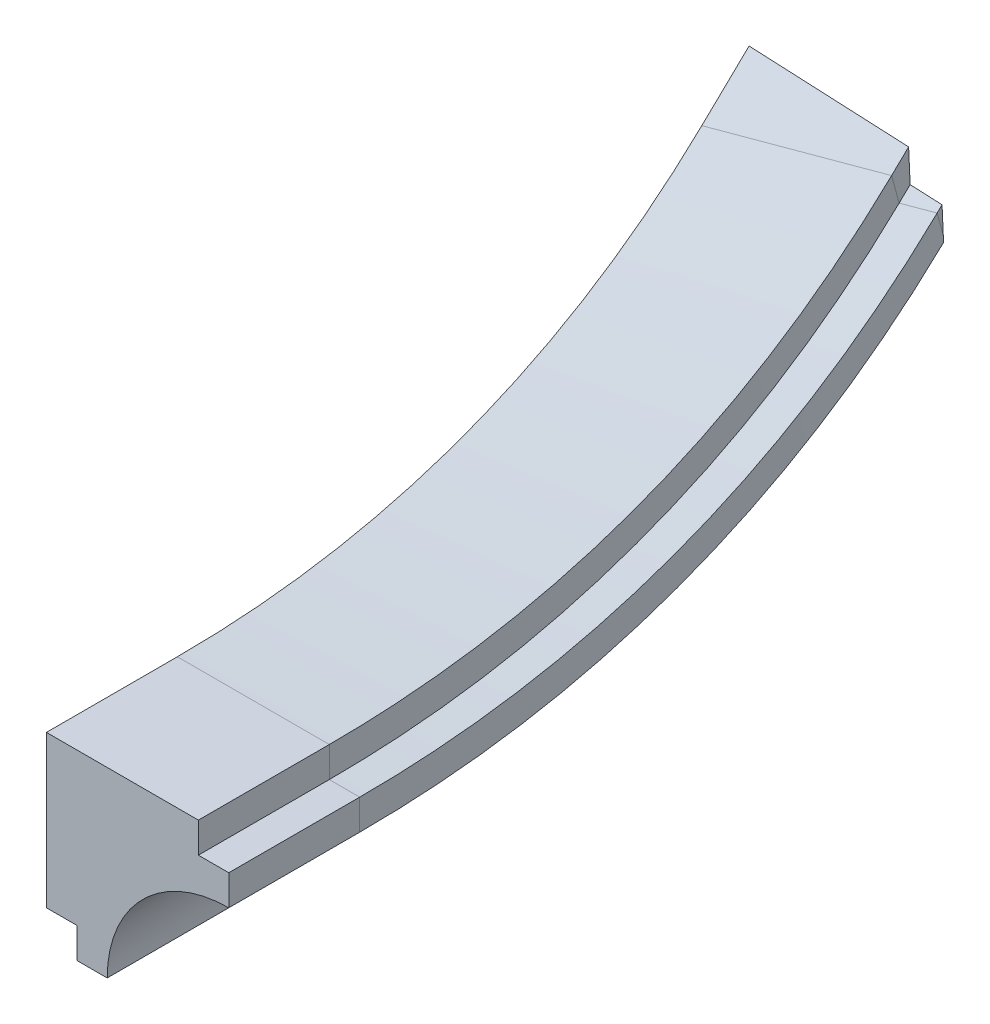
SolidWorks part; units mm, degrees
material "PET"
ref_plane "Front Plane" through (0, 0, 0) normal (0, 0, 1) x (1, 0, 0)
ref_plane "Top Plane" through (0, 0, 0) normal (0, 1, 0) x (1, 0, 0)
ref_plane "Right Plane" through (0, 0, 0) normal (1, 0, 0) x (0, 0, -1)
sketch "Sketch2" plane through (0, 0, 0) normal (0, 0, 1) x (1, 0, 0)
  line L0 (-150, 150) -> (150, 150) construction
  line L1 (-150, -150) -> (-150, 150) construction
  line L2 (-168.0217, 148.9959) -> (-150, 130) construction
  line L3 (-130, 150) -> (-130, 155)
  line L4 (-130, 155) -> (-135, 155)
  line L5 (-135, 155) -> (-135, 160)
  line L6 (160, 160) -> (-160, 160) construction
  line L7 (-135, 160) -> (-160, 160)
  line L8 (-160, 160) -> (-160, 135)
  line L9 (-160, -160) -> (-160, 160) construction
  line L10 (-160, 135) -> (-155, 135)
  line L11 (-155, 135) -> (-155, 130)
  line L12 (-155, 130) -> (-150, 130)
  arc A0 (-130, 150) -> (-150, 130) centre (-130, 130) ccw
  arc A1 (-130, 150) -> (-150, 130) centre (-130, 130) ccw construction
  dimension "D1" = 20
  dimension "D2" = 5
  dimension "D3" = 5
extrude "Boss-Extrude1" add sketch "Sketch2" against normal up to vertex (21.5428 mm away)
sketch "Sketch3" plane through (0, 0, -21.5428) normal (0, 0, -1) x (-1, 0, 0)
  line L8 (150, 130) -> (155, 130)
  line L9 (155, 130) -> (155, 135)
  line L10 (155, 135) -> (160, 135)
  line L11 (160, 135) -> (160, 160)
  line L12 (160, 160) -> (135, 160)
  line L13 (135, 160) -> (135, 155)
  line L14 (135, 155) -> (130, 155)
  line L15 (130, 155) -> (130, 150)
  line L16 (150, 130) -> (155, 130)
  line L17 (155, 130) -> (155, 135)
  line L18 (155, 135) -> (160, 135)
  line L19 (160, 135) -> (160, 160)
  line L20 (160, 160) -> (135, 160)
  line L21 (135, 160) -> (135, 155)
  line L22 (135, 155) -> (130, 155)
  line L23 (130, 155) -> (130, 150)
  arc A1 (150, 130) -> (130, 150) centre (130, 130) ccw
  arc A2 (150, 130) -> (130, 150) centre (130, 130) ccw
  dimension "D1" = 0
ref_plane "Plane1" through (0, 0, 0) normal (-0.7071, -0.7071, 0) x (-0.7071, 0.7071, 0)
sketch "Sketch4" plane through (0, 0, 0) normal (-0.7071, -0.7071, 0) x (-0.7071, 0.7071, 0)
  spline S0 degree 3 poles (-25.1571, 2217.2459) (2622.0798, 547.8019) (421.6327, 702.9942) (217.3761, 104.2548) (216.6258, 101.9585) (215.1851, 97.3434) (214.494, 95.0227) (212.5187, 88.0505) (211.3303, 83.3835) (208.1521, 69.3257) (206.5488, 59.8782) (168.6055, -275.987) (750.4958, -693.1834) (2828.6565, -1330.0872) knots -16.062495 -16.062495 -16.062495 -16.062495 0.25 0.25 0.3125 0.3125 0.375 0.375 0.5 0.5 0.75 0.75 9.315377 9.315377 9.315377 9.315377 only from (228.8934, 133.4429) to (203.8478, 21.5428) construction
  spline S1 degree 3 poles (228.8934, 133.4429) (224.8616, 124.6457) (221.2741, 115.6811) (217.3761, 104.2548) (216.6258, 101.9585) (215.1851, 97.3434) (214.494, 95.0227) (212.5187, 88.0505) (211.3303, 83.3835) (208.1521, 69.3257) (206.5488, 59.8782) (204.3967, 40.8282) (203.8478, 31.2258) (203.8478, 21.5428) knots 0 0 0 0 0.25 0.25 0.3125 0.3125 0.375 0.375 0.5 0.5 0.75 0.75 1 1 1 1
sweep "Sweep1" add profiles "Sketch3" path "Sketch4"
sketch "Sketch5" plane through (-63.8339, 63.8339, -196.9732) normal (-0.2946, 0.2946, -0.9091) x (-0.9556, -0.0908, 0.2803)
  line L8 (109.0945, 98.9823) -> (114.0888, 99.2201)
  line L9 (114.0888, 99.2201) -> (113.8509, 104.2145)
  line L10 (113.8509, 104.2145) -> (118.8453, 104.4523)
  line L11 (118.8453, 104.4523) -> (117.6559, 129.424)
  line L12 (117.6559, 129.424) -> (92.6842, 128.2347)
  line L13 (92.6842, 128.2347) -> (92.9221, 123.2403)
  line L14 (92.9221, 123.2403) -> (87.9277, 123.0024)
  line L15 (87.9277, 123.0024) -> (88.1656, 118.0081)
  line L16 (109.0945, 98.9823) -> (114.0888, 99.2201)
  line L17 (114.0888, 99.2201) -> (113.8509, 104.2145)
  line L18 (113.8509, 104.2145) -> (118.8453, 104.4523)
  line L19 (118.8453, 104.4523) -> (117.6559, 129.424)
  line L20 (117.6559, 129.424) -> (92.6842, 128.2347)
  line L21 (92.6842, 128.2347) -> (92.9221, 123.2403)
  line L22 (92.9221, 123.2403) -> (87.9277, 123.0024)
  line L23 (87.9277, 123.0024) -> (88.1656, 118.0081)
  arc A1 (109.0945, 98.9823) -> (88.1656, 118.0081) centre (89.1171, 98.0308) ccw
  arc A2 (109.0945, 98.9823) -> (88.1656, 118.0081) centre (89.1171, 98.0308) ccw
  dimension "D1" = 0
extrude "Boss-Extrude2" add sketch "Sketch5" along normal blind 20
sketch "Sketch6" plane through (0, 0, 0) normal (0, 1, 0) x (1, 0, 0)
  line L0 (-132.8227, 135.6099) -> (-210.4864, 135.6099)
  line L1 (-148.9959, 135.6099) -> (148.9959, 135.6099) construction
  line L2 (-210.4864, 135.6099) -> (-168.8647, 181.5809)
  line L3 (-168.8647, 181.5809) -> (-132.8227, 135.6099)
extrude "Cut-Extrude1" cut sketch "Sketch6" against normal through all both and the other way through all
